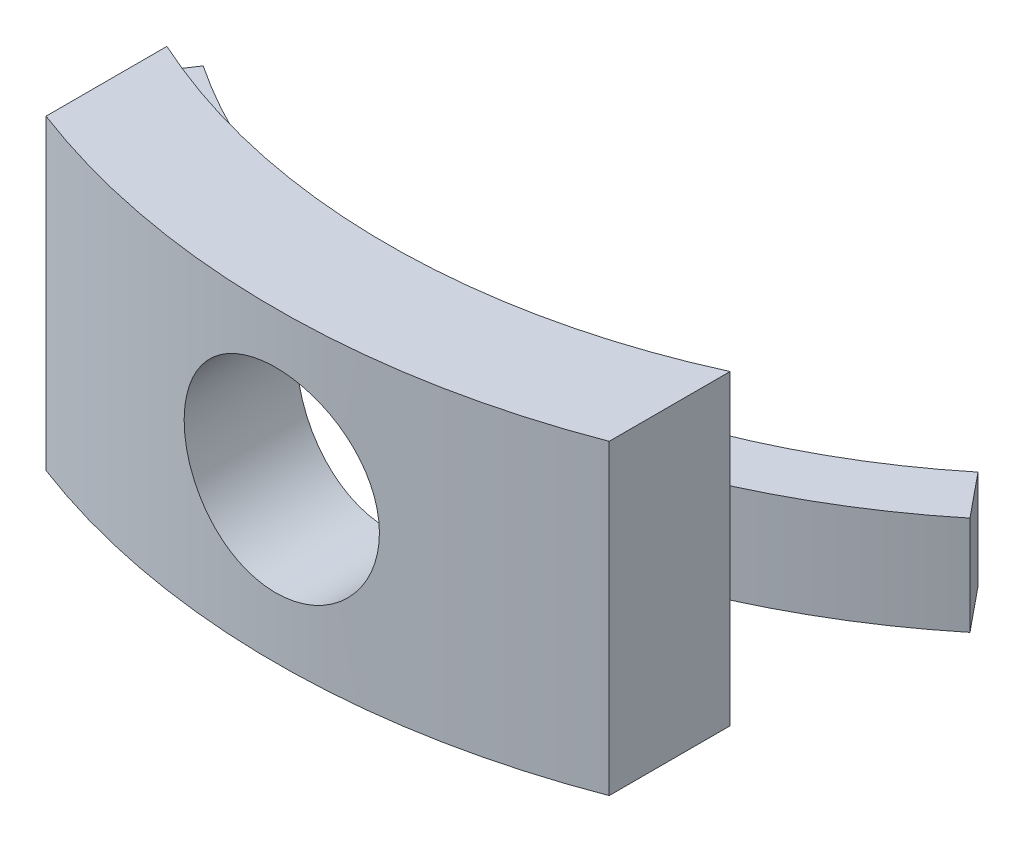
SolidWorks part; units mm, degrees
ref_plane "Front Plane" through (0, 0, 0) normal (0, 0, 1) x (1, 0, 0)
ref_plane "Top Plane" through (0, 0, 0) normal (0, 1, 0) x (1, 0, 0)
ref_plane "Right Plane" through (0, 0, 0) normal (1, 0, 0) x (0, 0, -1)
sketch "Sketch1" plane through (0, 0, 0) normal (0, 1, 0) x (1, 0, 0)
  circle A0 centre (0, 0) radius 79.8711
  circle A1 centre (0, 0) radius 68.5951
extrude "Boss-Extrude1" add sketch "Sketch1" along normal blind 31
sketch "Sketch2" plane through (0, 31, 0) normal (0, 1, 0) x (1, 0, 0)
  line L1 (-28.4484, -45.7331) -> (28.4484, -45.7331)
  line L2 (-28.4484, -45.7331) -> (-28.4484, -91.457)
  line L3 (-28.4484, -91.457) -> (28.4484, -91.457)
  line L4 (28.4484, -45.7331) -> (28.4484, -91.457)
  line L5 (-28.4484, -45.7331) -> (28.4484, -91.457) construction
  line L6 (-28.4484, -91.457) -> (28.4484, -45.7331) construction
  line L7 (-126.7374, 96.5509) -> (106.4595, 96.5509)
  line L8 (-126.7374, 96.5509) -> (-126.7374, -126.0461)
  line L9 (-126.7374, -126.0461) -> (106.4595, -126.0461)
  line L10 (106.4595, 96.5509) -> (106.4595, -126.0461)
  circle A0 centre (0, 0) radius 68.5951 construction
  point P0 (0, -68.5951)
extrude "Cut-Extrude1" cut sketch "Sketch2" against normal blind 31
ref_plane "Plane1" through (0, 16, 0) normal (0, 1, 0) x (1, 0, 0)
sketch "Sketch4" plane through (0, 16, 0) normal (0, 1, 0) x (1, 0, 0)
  line L0 (43.3923, -53.1262) -> (39.7738, -48.6959)
  line L1 (-34.9096, -52.2931) -> (-38.0856, -57.0506)
  arc A0 (-38.0856, -57.0506) -> (43.3923, -53.1262) centre (0, 0) ccw
  arc A1 (-34.9096, -52.2931) -> (39.7738, -48.6959) centre (0, 0) ccw
extrude "Boss-Extrude2" add sketch "Sketch4" along normal mid plane 10
sketch "Sketch5" plane through (0, 21, 0) normal (0, 1, 0) x (1, 0, 0)
  line L0 (20.3657, -65.5021) -> (20.3657, -59.4852)
  line L1 (20.3657, -59.4852) -> (-20.3657, -59.4852)
  line L2 (-20.3657, -59.4852) -> (-20.3657, -65.5021)
  line L5 (-34.9096, -52.2931) -> (-38.0856, -57.0506)
  line L6 (43.3923, -53.1262) -> (39.7738, -48.6959)
  arc A0 (-28.4484, -62.4178) -> (28.4484, -62.4178) centre (0, 0) ccw construction
  arc A1 (-34.9096, -52.2931) -> (39.7738, -48.6959) centre (0, 0) ccw construction
  arc A2 (-28.4484, -62.4178) -> (28.4484, -62.4178) centre (0, 0) ccw construction
  arc A7 (-34.9096, -52.2931) -> (39.7738, -48.6959) centre (0, 0) ccw
  arc A8 (-38.0856, -57.0506) -> (-28.4484, -62.4178) centre (0, 0) ccw
  arc A9 (-34.9096, -52.2931) -> (39.7738, -48.6959) centre (0, 0) ccw
  arc A10 (-28.4484, -62.4178) -> (28.4484, -62.4178) centre (0, 0) ccw
  arc A15 (-28.4484, -62.4178) -> (28.4484, -62.4178) centre (0, 0) ccw
  arc A16 (28.4484, -62.4178) -> (43.3923, -53.1262) centre (0, 0) ccw
  arc M7 (39.7738, -48.6959) -> (-34.9096, -52.2931) centre (0, 0) cw
  arc M10 (-28.4484, -62.4178) -> (28.4484, -62.4178) centre (0, 0) ccw
  dimension "D1" = 0
extrude "Cut-Extrude3" cut sketch "Sketch5" against normal blind 18 contours L2 L0 M7 M10
sketch "Sketch6" plane through (0, 0, 0) normal (0, 0, 1) x (1, 0, 0)
  line L0 (55, 16) -> (-55, 16) construction
  circle A0 centre (0, 16) radius 9.8626
extrude "Cut-Extrude4" cut sketch "Sketch6" along normal blind 128
